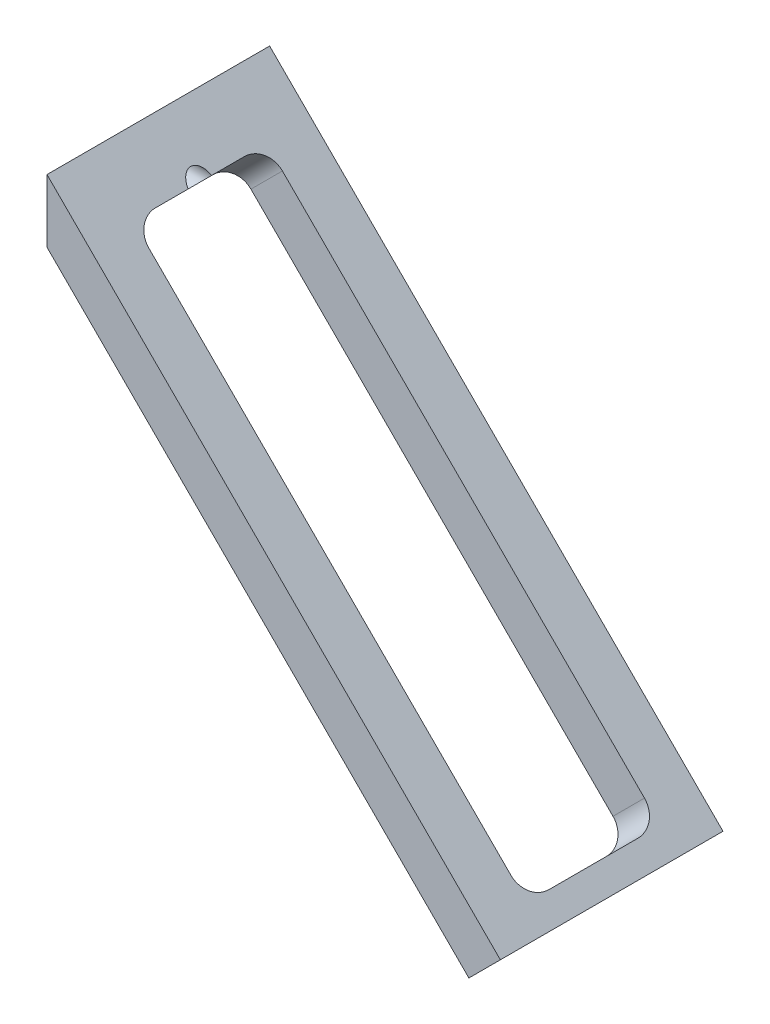
SolidWorks part; units mm, degrees
ref_plane "Front" through (0, 0, 0) normal (0, 0, 1) x (1, 0, 0)
ref_plane "Top" through (0, 0, 0) normal (0, 1, 0) x (1, 0, 0)
ref_plane "Right" through (0, 0, 0) normal (1, 0, 0) x (0, 0, -1)
sketch "Sketch1" plane through (0, 0, 0) normal (0, 0, 1) x (1, 0, 0)
  line L0 (-32.3289, 32.3289) -> (-32.3289, 23.3487)
  line L1 (-32.3289, 23.3487) -> (27.8388, -36.8191)
  line L3 (-32.3289, 32.3289) -> (32.3289, -32.3289)
  line L4 (27.8388, -36.8191) -> (32.3289, -32.3289)
  line L5 (0, -50) -> (0, 50) construction
  line L6 (50, 0) -> (-50, 0) construction
  point P4 (0, 0)
  dimension "D1" = 6.35
  dimension "D2" = 45
  dimension "D3" = 91.44
extrude "Boss-Extrude1" add sketch "Sketch1" along normal mid plane 31.75 contours L3 L4 L1 L0
sketch "Sketch2" plane through (0, 0, 0) normal (0.7071, 0.7071, 0) x (0, 0, -1)
  line L0 (0, 50) -> (0, -50) construction
  line L1 (-9.525, -42.037) -> (9.525, -42.037)
  line L2 (-9.525, -42.037) -> (-9.525, 37.338)
  line L3 (-9.525, 37.338) -> (9.525, 37.338)
  line L4 (9.525, -42.037) -> (9.525, 37.338)
  line L5 (-9.525, -42.037) -> (9.525, 37.338) construction
  line L6 (-9.525, 37.338) -> (9.525, -42.037) construction
  line L7 (-15.875, 45.72) -> (15.875, 45.72) construction
  point P0 (0, -2.3495)
  dimension "D1" = 79.375
  dimension "D2" = 19.05
  dimension "D3" = 8.382
extrude "Cut-Extrude1" cut sketch "Sketch2" against normal blind 12.7 contours L1 L4 L3 L2
fillet "Fillet1" radius 3.175 4 edges at (27.4796, -31.9697, 9.525) (27.4796, -31.9697, -9.525) (-28.647, 24.1569, -9.525) (-28.647, 24.1569, 9.525)
sketch "Sketch3" plane through (29.7246, -29.7246, 0) normal (-0.7071, 0.7071, 0) x (0, 0, 1)
  line L0 (0, -50) -> (0, 50) construction
  line L1 (6.35, -6.35) -> (6.35, 0) construction
  point P0 (0, -3.175)
  point P6 (6.35, -3.175)
hole_wizard "#8 Clearance Hole1" positions "Sketch4" profile "Sketch6" hole size "#8" standard "ANSI Inch"
sketch "Sketch4" plane through (29.7246, -29.7246, 0) normal (-0.7071, 0.7071, 0) x (0, 0, 1)
  point P0 (0, -3.175)
sketch "Sketch6" plane through (27.4796, -31.9697, 0) normal (0, 0, 1) x (-0.7071, -0.7071, 0)
  line L0 (0, 0) -> (0, 17.8607)
  line L1 (0, 17.8607) -> (2.2479, 16.51)
  line L2 (2.2479, 16.51) -> (2.2479, 0)
  line L5 (2.2479, 0) -> (0, 0)
  line L10 (0, 17.8607) -> (-2.2479, 16.51) construction
  line L11 (0, -6.35) -> (0, 107.95) construction
  dimension "Hole Dia." = 4.4958
  dimension "Hole Depth" = 16.51
  dimension "Drill Angle" = 118
sketch "Sketch7" plane through (-32.3289, 0, 0) normal (-1, 0, 0) x (0, 0, 1)
  point P0 (0, 25.9789)
hole_wizard "#8-32 Tapped Hole1" positions "Sketch8" profile "Sketch10" tap size "#8-32" standard "ANSI Inch" end condition up to next
sketch "Sketch8" plane through (-32.3289, 0, 0) normal (-1, 0, 0) x (0, 0, 1)
  point P0 (0, 25.9789)
cosmetic thread "Hole Thread1" parameters "D2"=4.1656
sketch "Sketch10" plane through (-32.3289, 25.9789, 0) normal (0, 1, 0) x (0, 0, 1)
  line L0 (0, 0) -> (0, 5.5039)
  line L1 (0, 5.5039) -> (1.7272, 5.5039)
  line L2 (1.7272, 5.5039) -> (1.7272, 0)
  line L5 (1.7272, 0) -> (0, 0)
  line L11 (0, -6.35) -> (0, 107.95) construction
  dimension "Thru Tap Drill Dia." = 3.4544
  dimension "Thru Tap Drill Depth" = 5.5039
ref_plane "Plane1" through (-32.3289, 23.3487, 15.875) normal (0.7071, -0.7071, 0) x (0, 0, -1)
